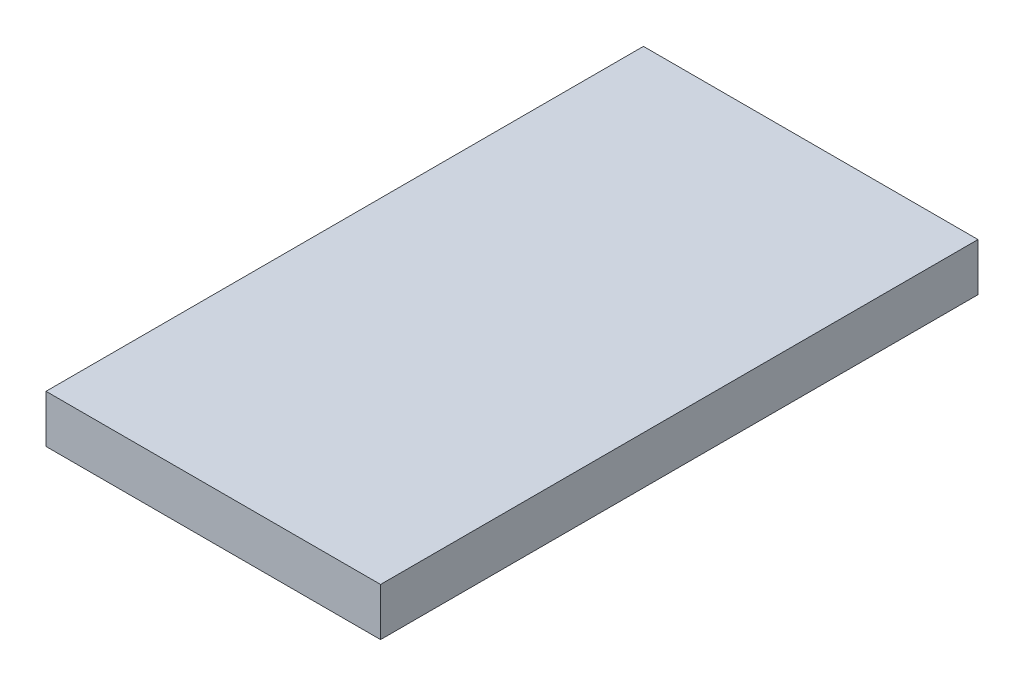
SolidWorks part; units mm, degrees
ref_plane "Front Plane" through (0, 0, 0) normal (0, 0, 1) x (1, 0, 0)
ref_plane "Top Plane" through (0, 0, 0) normal (0, 1, 0) x (1, 0, 0)
ref_plane "Right Plane" through (0, 0, 0) normal (1, 0, 0) x (0, 0, -1)
sketch "Sketch1" plane through (0, 0, 0) normal (0, 1, 0) x (1, 0, 0)
  line L1 (0, 0) -> (44.45, 0)
  line L2 (0, 0) -> (0, 79.375)
  line L3 (0, 79.375) -> (44.45, 79.375)
  line L4 (44.45, 0) -> (44.45, 79.375)
  dimension "D1" = 44.45
  dimension "D2" = 79.375
extrude "Boss-Extrude1" add sketch "Sketch1" along normal blind 6.35
